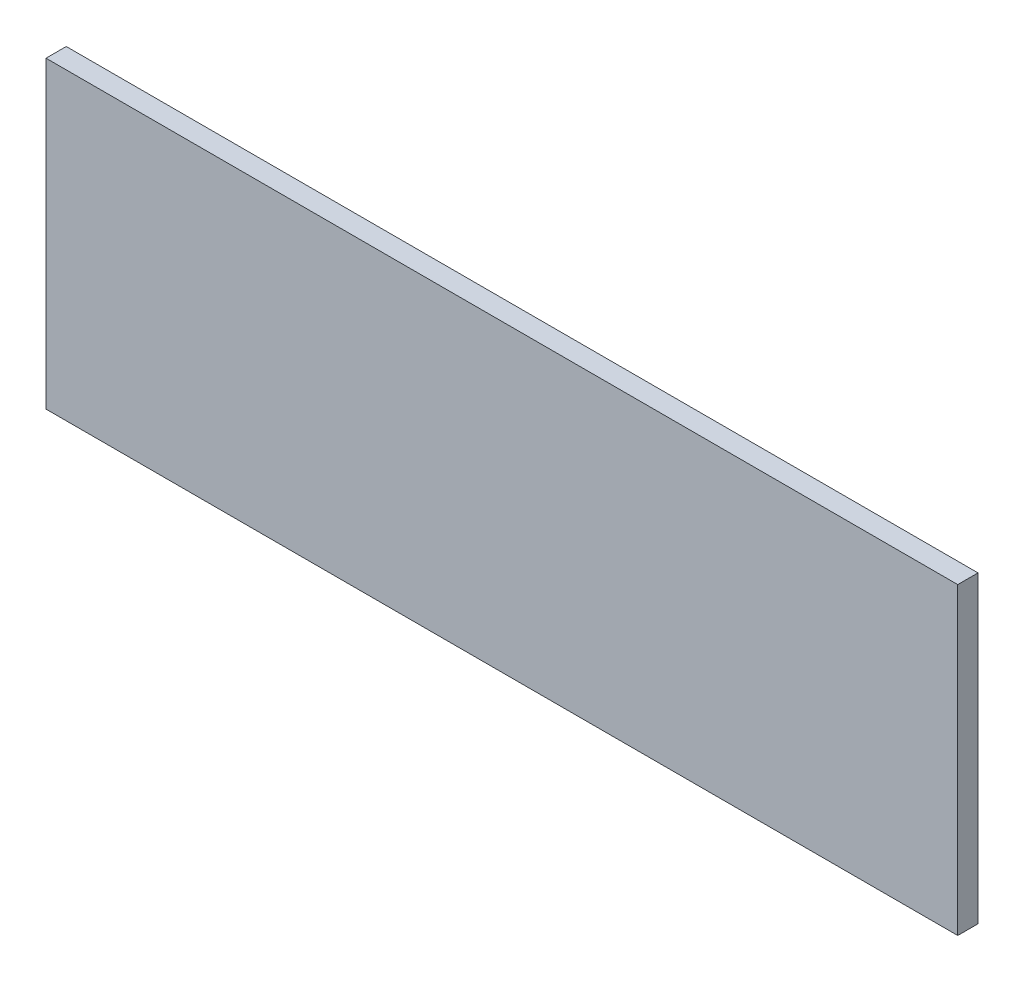
SolidWorks part; units mm, degrees
ref_plane "Спереди" through (0, 0, 0) normal (0, 0, 1) x (1, 0, 0)
ref_plane "Сверху" through (0, 0, 0) normal (0, 1, 0) x (1, 0, 0)
ref_plane "Справа" through (0, 0, 0) normal (1, 0, 0) x (0, 0, -1)
sketch "Эскиз1" plane through (0, 0, 0) normal (0, 1, 0) x (1, 0, 0)
  line L1 (-45, 1) -> (45, 1)
  line L2 (-45, 1) -> (-45, -1)
  line L3 (-45, -1) -> (45, -1)
  line L4 (45, 1) -> (45, -1)
  line L5 (-45, 1) -> (45, -1) construction
  line L6 (-45, -1) -> (45, 1) construction
  point P0 (0, 0)
  dimension "D1" = 2
  dimension "D2" = 90
extrude "Бобышка-Вытянуть1" add sketch "Эскиз1" along normal blind 30
